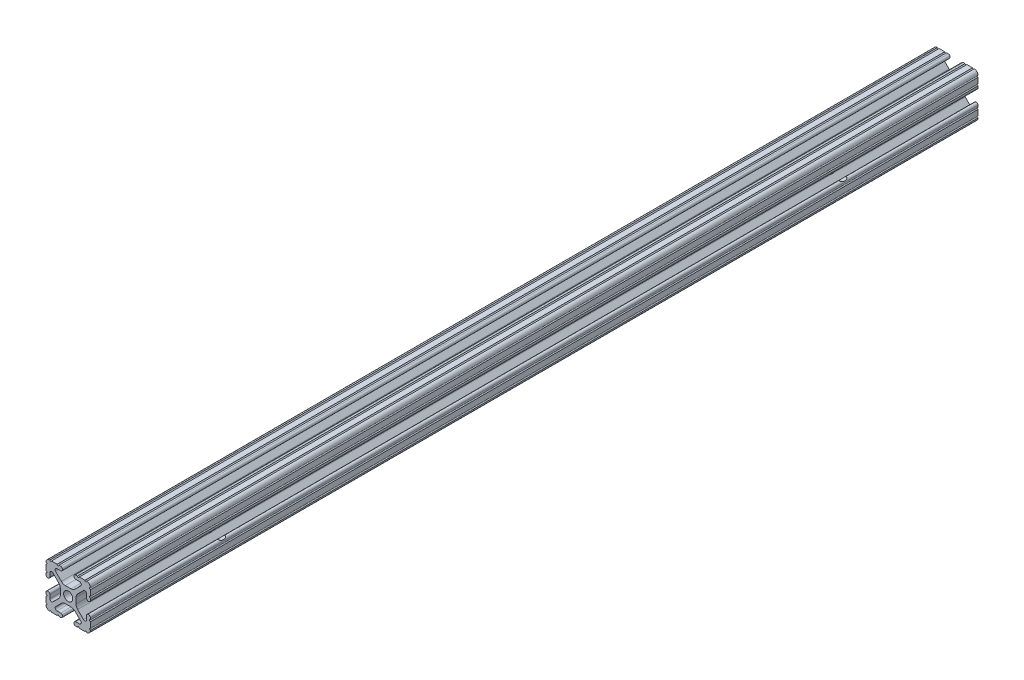
SolidWorks part; units mm, degrees
ref_plane "Front Plane" through (0, 0, 0) normal (0, 0, 1) x (1, 0, 0)
ref_plane "Top Plane" through (0, 0, 0) normal (0, 1, 0) x (1, 0, 0)
ref_plane "Right Plane" through (0, 0, 0) normal (1, 0, 0) x (0, 0, -1)
ref_plane "Plane1" through (0, 0, -25.4) normal (0, 0, -1) x (-1, 0, 0)
sketch "Sketch1" plane through (0, 0, -25.4) normal (0, 0, -1) x (-1, 0, 0)
  line L0 (12.7, -9.5504) -> (12.7, -6.3331)
  line L1 (12.7, -5.3171) -> (12.7, -4.3434)
  line L2 (10.4902, -4.3434) -> (10.4902, -6.4748)
  line L3 (8.7558, -7.1932) -> (5.4257, -3.8632)
  line L4 (4.4958, -1.6181) -> (4.4958, 1.6181)
  line L5 (5.4257, 3.8632) -> (8.7558, 7.1932)
  line L6 (10.4902, 6.4748) -> (10.4902, 4.3434)
  line L7 (12.7, 4.3434) -> (12.7, 5.3171)
  line L8 (12.7, 6.3331) -> (12.7, 9.5504)
  line L9 (9.5504, 12.7) -> (6.3331, 12.7)
  line L10 (5.3171, 12.7) -> (4.3434, 12.7)
  line L11 (4.3434, 10.4902) -> (6.4748, 10.4902)
  line L12 (7.1932, 8.7558) -> (3.8632, 5.4257)
  line L13 (1.6181, 4.4958) -> (-1.6181, 4.4958)
  line L14 (-3.8632, 5.4257) -> (-7.1932, 8.7558)
  line L15 (-6.4748, 10.4902) -> (-4.3434, 10.4902)
  line L16 (-4.3434, 12.7) -> (-5.3171, 12.7)
  line L17 (-6.3331, 12.7) -> (-9.5504, 12.7)
  line L18 (-12.7, 9.5504) -> (-12.7, 6.3331)
  line L19 (-12.7, 5.3171) -> (-12.7, 4.3434)
  line L20 (-10.4902, 4.3434) -> (-10.4902, 6.4748)
  line L21 (-8.7558, 7.1932) -> (-5.4257, 3.8632)
  line L22 (-4.4958, 1.6181) -> (-4.4958, -1.6181)
  line L23 (-5.4257, -3.8632) -> (-8.7558, -7.1932)
  line L24 (-10.4902, -6.4748) -> (-10.4902, -4.3434)
  line L25 (-12.7, -4.3434) -> (-12.7, -5.3171)
  line L26 (-12.7, -6.3331) -> (-12.7, -9.5504)
  line L27 (-9.5504, -12.7) -> (-6.3331, -12.7)
  line L28 (-5.3171, -12.7) -> (-4.3434, -12.7)
  line L29 (-4.3434, -10.4902) -> (-6.4748, -10.4902)
  line L30 (-7.1932, -8.7558) -> (-3.8632, -5.4257)
  line L31 (-1.6181, -4.4958) -> (1.6181, -4.4958)
  line L32 (3.8632, -5.4257) -> (7.1932, -8.7558)
  line L33 (6.4748, -10.4902) -> (4.3434, -10.4902)
  line L34 (4.3434, -12.7) -> (5.3171, -12.7)
  line L35 (6.3331, -12.7) -> (9.5504, -12.7)
  arc A0 (12.6998, -10.5664) -> (12.7, -9.5504) centre (12.7, -10.0584) cw
  arc A1 (12.7, -6.3331) -> (12.7, -5.3171) centre (12.7, -5.8251) cw
  arc A2 (12.7, -4.3434) -> (10.4902, -4.3434) centre (11.5951, -4.3434) ccw
  arc A3 (10.4902, -6.4748) -> (8.7558, -7.1932) centre (9.4742, -6.4748) cw
  arc A4 (5.4257, -3.8632) -> (4.4958, -1.6181) centre (7.6708, -1.6181) cw
  arc A5 (4.4958, 1.6181) -> (5.4257, 3.8632) centre (7.6708, 1.6181) cw
  arc A6 (8.7558, 7.1932) -> (10.4902, 6.4748) centre (9.4742, 6.4748) cw
  arc A7 (10.4902, 4.3434) -> (12.7, 4.3434) centre (11.5951, 4.3434) ccw
  arc A8 (12.7, 5.3171) -> (12.7, 6.3331) centre (12.7, 5.8251) cw
  arc A9 (12.7, 9.5504) -> (12.6998, 10.5664) centre (12.7, 10.0584) cw
  arc A10 (12.6998, 10.5664) -> (10.5664, 12.6998) centre (10.5918, 10.5918) ccw
  arc A11 (10.5664, 12.6998) -> (9.5504, 12.7) centre (10.0584, 12.7) cw
  arc A12 (6.3331, 12.7) -> (5.3171, 12.7) centre (5.8251, 12.7) cw
  arc A13 (4.3434, 12.7) -> (4.3434, 10.4902) centre (4.3434, 11.5951) ccw
  arc A14 (6.4748, 10.4902) -> (7.1932, 8.7558) centre (6.4748, 9.4742) cw
  arc A15 (3.8632, 5.4257) -> (1.6181, 4.4958) centre (1.6181, 7.6708) cw
  arc A16 (-1.6181, 4.4958) -> (-3.8632, 5.4257) centre (-1.6181, 7.6708) cw
  arc A17 (-7.1932, 8.7558) -> (-6.4748, 10.4902) centre (-6.4748, 9.4742) cw
  arc A18 (-4.3434, 10.4902) -> (-4.3434, 12.7) centre (-4.3434, 11.5951) ccw
  arc A19 (-5.3171, 12.7) -> (-6.3331, 12.7) centre (-5.8251, 12.7) cw
  arc A20 (-9.5504, 12.7) -> (-10.5664, 12.6998) centre (-10.0584, 12.7) cw
  arc A21 (-10.5664, 12.6998) -> (-12.6998, 10.5664) centre (-10.5918, 10.5918) ccw
  arc A22 (-12.6998, 10.5664) -> (-12.7, 9.5504) centre (-12.7, 10.0584) cw
  arc A23 (-12.7, 6.3331) -> (-12.7, 5.3171) centre (-12.7, 5.8251) cw
  arc A24 (-12.7, 4.3434) -> (-10.4902, 4.3434) centre (-11.5951, 4.3434) ccw
  arc A25 (-10.4902, 6.4748) -> (-8.7558, 7.1932) centre (-9.4742, 6.4748) cw
  arc A26 (-5.4257, 3.8632) -> (-4.4958, 1.6181) centre (-7.6708, 1.6181) cw
  arc A27 (-4.4958, -1.6181) -> (-5.4257, -3.8632) centre (-7.6708, -1.6181) cw
  arc A28 (-8.7558, -7.1932) -> (-10.4902, -6.4748) centre (-9.4742, -6.4748) cw
  arc A29 (-10.4902, -4.3434) -> (-12.7, -4.3434) centre (-11.5951, -4.3434) ccw
  arc A30 (-12.7, -5.3171) -> (-12.7, -6.3331) centre (-12.7, -5.8251) cw
  arc A31 (-12.7, -9.5504) -> (-12.6998, -10.5664) centre (-12.7, -10.0584) cw
  arc A32 (-12.6998, -10.5664) -> (-10.5664, -12.6998) centre (-10.5918, -10.5918) ccw
  arc A33 (-10.5664, -12.6998) -> (-9.5504, -12.7) centre (-10.0584, -12.7) cw
  arc A34 (-6.3331, -12.7) -> (-5.3171, -12.7) centre (-5.8251, -12.7) cw
  arc A35 (-4.3434, -12.7) -> (-4.3434, -10.4902) centre (-4.3434, -11.5951) ccw
  arc A36 (-6.4748, -10.4902) -> (-7.1932, -8.7558) centre (-6.4748, -9.4742) cw
  arc A37 (-3.8632, -5.4257) -> (-1.6181, -4.4958) centre (-1.6181, -7.6708) cw
  arc A38 (1.6181, -4.4958) -> (3.8632, -5.4257) centre (1.6181, -7.6708) cw
  arc A39 (7.1932, -8.7558) -> (6.4748, -10.4902) centre (6.4748, -9.4742) cw
  arc A40 (4.3434, -10.4902) -> (4.3434, -12.7) centre (4.3434, -11.5951) ccw
  arc A41 (5.3171, -12.7) -> (6.3331, -12.7) centre (5.8251, -12.7) cw
  arc A42 (9.5504, -12.7) -> (10.5664, -12.6998) centre (10.0584, -12.7) cw
  arc A43 (10.5664, -12.6998) -> (12.6998, -10.5664) centre (10.5918, -10.5918) ccw
  circle A44 centre (0, 0) radius 2.6035
extrude "MainExtrude" add sketch "Sketch1" along normal blind 508
sketch "Sketch3" plane through (0, 0, 0) normal (1, 0, 0) x (0, 0, -1)
  line L0 (533.4, -1.6181) -> (533.4, 1.6181) construction
  circle A0 centre (101.6, 0) radius 3.81
  circle A1 centre (457.2, 0) radius 3.81
  dimension "D2" = 7.62
  dimension "D4" = 7.62
  dimension "D1" = 76.2
  dimension "D3" = 76.2
extrude "FrameSupportHoles" cut sketch "Sketch3" against normal up to surface and the other way up to surface up to face at (-12.7, 7.9417, -279.4) other way up to face at (12.7, 7.9417, -279.4)
sketch "Sketch4" plane through (-12.7, 0, 0) normal (-1, 0, 0) x (0, 0, 1)
  circle A0 centre (-101.6, 0) radius 10.3187
  dimension "D1" = 20.6375
extrude "CounterBore" cut sketch "Sketch4" against normal up to surface (2.2098 mm away) up to face at (-10.4902, 5.4091, -279.4)
